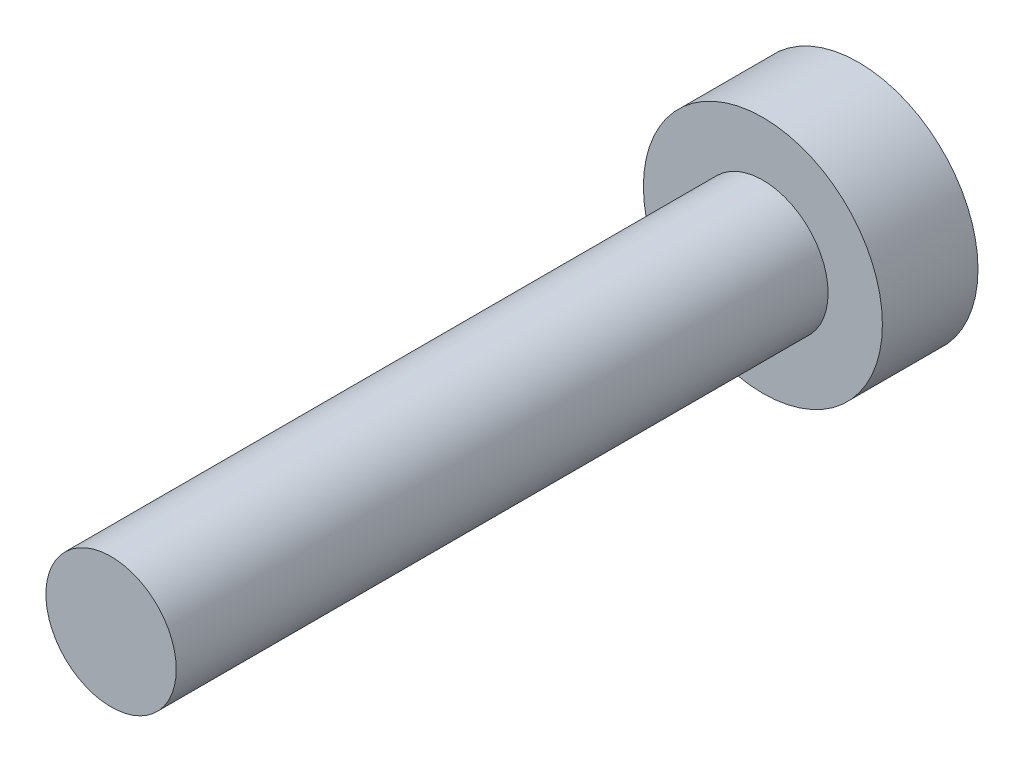
SolidWorks part; units mm, degrees
material "AISI 304"
ref_plane "前视基准面" through (0, 0, 0) normal (0, 0, 1) x (1, 0, 0)
ref_plane "上视基准面" through (0, 0, 0) normal (0, 1, 0) x (1, 0, 0)
ref_plane "右视基准面" through (0, 0, 0) normal (1, 0, 0) x (0, 0, -1)
sketch "草图1" plane through (0, 0, 0) normal (0, 0, 1) x (1, 0, 0)
  circle A0 centre (0, 0) radius 2.75
  dimension "D1" = 5.5
extrude "凸台-拉伸1" add sketch "草图1" along normal blind 2.2
sketch "草图2" plane through (0, 0, 2.2) normal (0, 0, 1) x (1, 0, 0)
  circle A0 centre (0, 0) radius 1.5
  dimension "D1" = 3
extrude "凸台-拉伸2" add sketch "草图2" along normal blind 15
